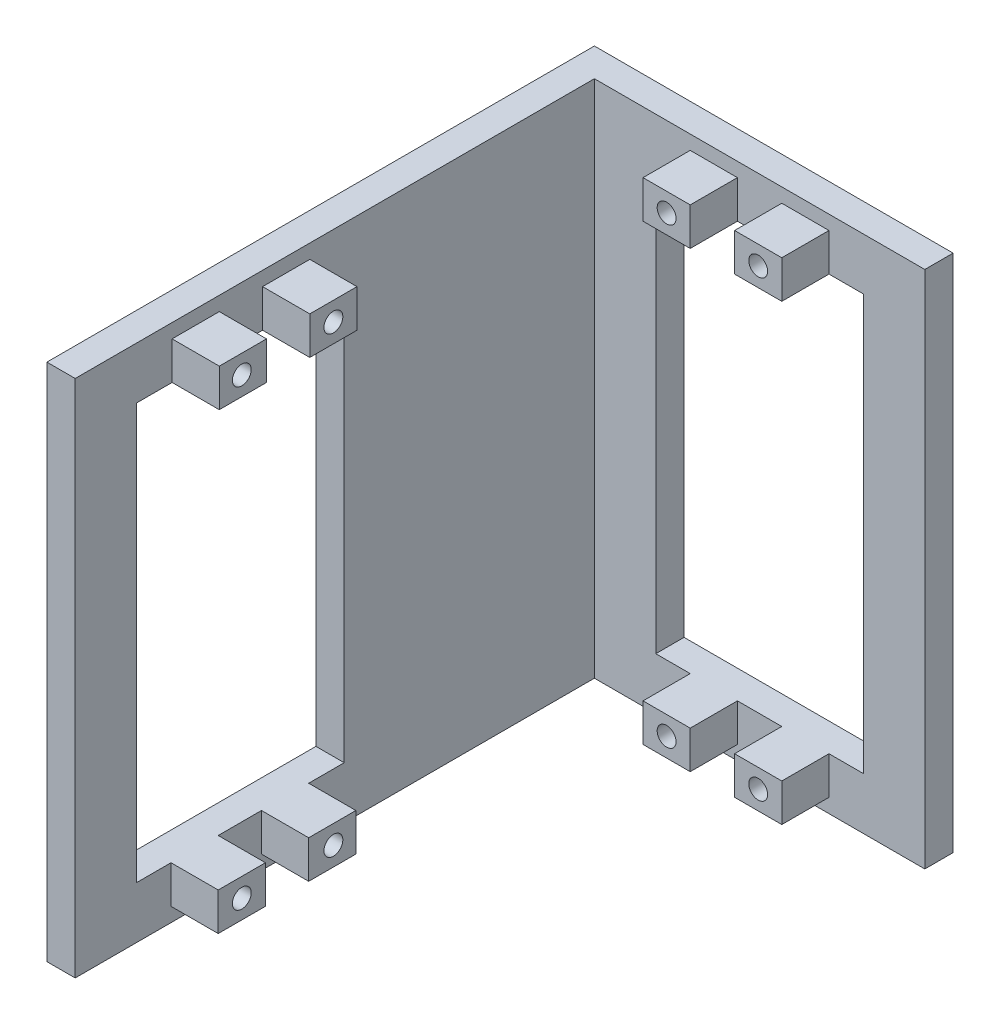
SolidWorks part; units mm, degrees
material "Polylactic Acid"
ref_plane "Front Plane" through (0, 0, 0) normal (0, 0, 1) x (1, 0, 0)
ref_plane "Top Plane" through (0, 0, 0) normal (0, 1, 0) x (1, 0, 0)
ref_plane "Right Plane" through (0, 0, 0) normal (1, 0, 0) x (0, 0, -1)
sketch "Sketch1" plane through (0, 0, 0) normal (0, 1, 0) x (1, 0, 0)
  line L0 (38, 0) -> (0, 0)
  line L1 (0, 0) -> (0, -58)
  line L2 (0, -58) -> (3, -58)
  line L3 (3, -58) -> (3, -3)
  line L4 (3, -3) -> (38, -3)
  line L5 (38, -3) -> (38, 0)
  dimension "D1" = 3
  dimension "D2" = 58
  dimension "D3" = 38
extrude "Boss-Extrude1" add sketch "Sketch1" along normal mid plane 55
sketch "Sketch3" plane through (0, 0, 3) normal (0, 0, 1) x (1, 0, 0)
  line L0 (15.65, -24) -> (25.35, -24) construction
  line L1 (15.65, -24) -> (15.65, 24) construction
  line L2 (3, -27.5) -> (38, -27.5) construction
  line L3 (9.5, -22) -> (31.5, -22)
  line L4 (9.5, -22) -> (9.5, 22)
  line L5 (9.5, 22) -> (31.5, 22)
  line L6 (31.5, -22) -> (31.5, 22)
  line L7 (38, 27.5) -> (38, -27.5) construction
  circle A0 centre (15.65, -24) radius 1
  circle A1 centre (25.35, -24) radius 1
  circle A2 centre (25.35, 24) radius 1
  circle A3 centre (15.65, 24) radius 1
  point P15 (20.5, -24)
  point P16 (20.5, -22)
  point P17 (15.65, 0)
  point P18 (9.5, 0)
  point P21 (20.5, -27.5)
  point P22 (31.5, 0)
  point P25 (38, 0)
  dimension "D5" = 2
  dimension "D3" = 9.7
  dimension "D4" = 48
  dimension "D6" = 22
  dimension "D7" = 44
  dimension "D1" = 2
  dimension "D2" = 2
extrude "Cut-Extrude1" cut sketch "Sketch3" against normal up to surface (3 mm away) up to face at (19, 0, 0)
sketch "Sketch4" plane through (3, 0, 0) normal (1, 0, 0) x (0, 0, -1)
  line L0 (-58, 27.5) -> (-58, -27.5) construction
  line L1 (-51.5, 22) -> (-29.5, 22)
  line L2 (-51.5, 22) -> (-51.5, -22)
  line L3 (-51.5, -22) -> (-29.5, -22)
  line L4 (-29.5, 22) -> (-29.5, -22)
  line L5 (-45.35, -24) -> (-35.65, -24) construction
  line L6 (-45.35, -24) -> (-45.35, 24) construction
  circle A0 centre (-45.35, -24) radius 1
  circle A1 centre (-35.65, -24) radius 1
  circle A2 centre (-35.65, 24) radius 1
  circle A3 centre (-45.35, 24) radius 1
  point P6 (-51.5, 0)
  point P7 (-58, 0)
  point P10 (-40.5, -22)
  point P12 (-40.5, -24)
  point P21 (-45.35, 0)
  dimension "D8" = 2
  dimension "D1" = 6.5
  dimension "D2" = 22
  dimension "D3" = 44
  dimension "D6" = 9.7
  dimension "D7" = 48
  dimension "D4" = 2
  dimension "D5" = 2
extrude "Cut-Extrude2" cut sketch "Sketch4" against normal up to surface (3 mm away) up to face at (0, 0, 29)
sketch "Sketch5" plane through (3, 0, 0) normal (1, 0, 0) x (0, 0, -1)
  line L0 (-51.5, -22) -> (-29.5, -22) construction
  line L32 (-47.85, -26) -> (-42.85, -26)
  line L33 (-47.85, -26) -> (-47.85, -22)
  line L34 (-47.85, -22) -> (-42.85, -22)
  line L35 (-42.85, -26) -> (-42.85, -22)
  line L36 (-47.85, -26) -> (-42.85, -22) construction
  line L37 (-47.85, -22) -> (-42.85, -26) construction
  line L38 (-38.2653, -26) -> (-33.2653, -26)
  line L39 (-38.2653, -26) -> (-38.2653, -22)
  line L40 (-38.2653, -22) -> (-33.2653, -22)
  line L41 (-33.2653, -26) -> (-33.2653, -22)
  line L42 (-38.2653, -26) -> (-33.2653, -22) construction
  line L43 (-38.2653, -22) -> (-33.2653, -26) construction
  line L44 (-38.15, 22) -> (-33.15, 22)
  line L45 (-38.15, 22) -> (-38.15, 26)
  line L46 (-38.15, 26) -> (-33.15, 26)
  line L47 (-33.15, 22) -> (-33.15, 26)
  line L48 (-38.15, 22) -> (-33.15, 26) construction
  line L49 (-38.15, 26) -> (-33.15, 22) construction
  line L50 (-47.7347, 22) -> (-42.7347, 22)
  line L51 (-47.7347, 22) -> (-47.7347, 26)
  line L52 (-47.7347, 26) -> (-42.7347, 26)
  line L53 (-42.7347, 22) -> (-42.7347, 26)
  line L54 (-47.7347, 22) -> (-42.7347, 26) construction
  line L55 (-47.7347, 26) -> (-42.7347, 22) construction
  line L56 (-45.35, -24) -> (-35.7653, -24) construction
  line L57 (-45.35, -24) -> (-45.2347, 24) construction
  circle A0 centre (-35.65, 24) radius 1 construction
  point P0 (-45.35, -24)
  point P9 (-35.2026, 20.2401)
  point P10 (-35.7659, 18.3376)
  point P15 (0, 0)
  point P16 (-35.7653, -24)
  point P21 (-35.65, 24)
  point P26 (-45.2347, 24)
  dimension "D1" = 2
  dimension "D2" = 2
  dimension "D3" = 5
extrude "Boss-Extrude2" add sketch "Sketch5" along normal blind 5
sketch "Sketch6" plane through (3, 0, 0) normal (-1, 0, 0) x (0, 0, 1)
  line L0 (35.65, -24) -> (45.35, -24) construction
  line L1 (35.65, -24) -> (35.65, 24) construction
  circle A0 centre (35.65, -24) radius 1
  circle A1 centre (45.35, -24) radius 1
  circle A2 centre (45.35, 24) radius 1
  circle A3 centre (35.65, 24) radius 1
  circle A4 centre (35.65, -24) radius 1 construction
  point P3 (45.65, -14)
  point P4 (45.35, 24)
  dimension "D1" = 2
  dimension "D2" = 2
extrude "Cut-Extrude3" cut sketch "Sketch6" against normal up to surface (5 mm away) up to face at (8, 24, 45.2347)
sketch "Sketch7" plane through (0, 0, 3) normal (0, 0, 1) x (1, 0, 0)
  line L0 (9.5, -22) -> (31.5, -22) construction
  line L1 (13.15, -26) -> (18.15, -26)
  line L2 (13.15, -26) -> (13.15, -22)
  line L3 (13.15, -22) -> (18.15, -22)
  line L4 (18.15, -26) -> (18.15, -22)
  line L5 (13.15, -26) -> (18.15, -22) construction
  line L6 (13.15, -22) -> (18.15, -26) construction
  line L7 (22.85, -26) -> (27.85, -26)
  line L8 (22.85, -26) -> (22.85, -22)
  line L9 (22.85, -22) -> (27.85, -22)
  line L10 (27.85, -26) -> (27.85, -22)
  line L11 (22.85, -26) -> (27.85, -22) construction
  line L12 (22.85, -22) -> (27.85, -26) construction
  line L13 (22.85, 22) -> (27.85, 22)
  line L14 (22.85, 22) -> (22.85, 26)
  line L15 (22.85, 26) -> (27.85, 26)
  line L16 (27.85, 22) -> (27.85, 26)
  line L17 (22.85, 22) -> (27.85, 26) construction
  line L18 (22.85, 26) -> (27.85, 22) construction
  line L19 (13.15, 22) -> (18.15, 22)
  line L20 (13.15, 22) -> (13.15, 26)
  line L21 (13.15, 26) -> (18.15, 26)
  line L22 (18.15, 22) -> (18.15, 26)
  line L23 (13.15, 22) -> (18.15, 26) construction
  line L24 (13.15, 26) -> (18.15, 22) construction
  line L25 (15.65, -24) -> (25.35, -24) construction
  line L26 (15.65, -24) -> (15.65, 24) construction
  line L27 (15.65, -24) -> (25.35, -24) construction
  line L28 (15.65, -24) -> (15.65, 24) construction
  circle A0 centre (25.35, 24) radius 1 construction
  circle A1 centre (15.65, -24) radius 1
  circle A2 centre (15.65, -24) radius 1 construction
  circle A3 centre (25.35, -24) radius 1
  circle A4 centre (25.35, 24) radius 1
  circle A5 centre (15.65, 24) radius 1
  point P0 (15.65, -24)
  point P9 (25.35, -24)
  point P15 (25.35, 24)
  point P20 (15.65, 24)
  point P31 (22.7338, -12.9727)
  point P33 (0, 0)
  point P34 (25.35, 24)
  point P38 (0, 0)
  point P39 (0, 0)
  point P42 (25.1284, -24.1773)
  dimension "D1" = 5
  dimension "D2" = 2
  dimension "D3" = 2
extrude "Boss-Extrude3" add sketch "Sketch7" along normal blind 5
